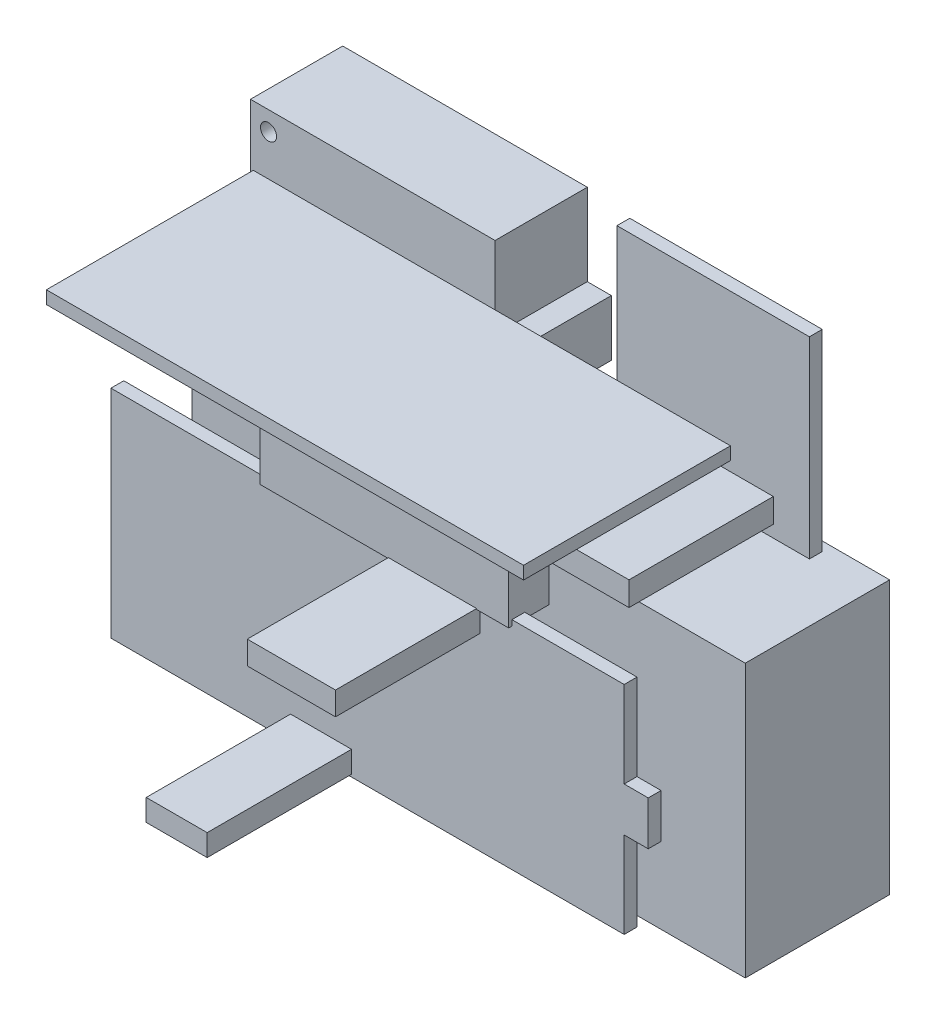
SolidWorks part; units mm, degrees
ref_plane "前视基准面" through (0, 0, 0) normal (0, 0, 1) x (1, 0, 0)
ref_plane "上视基准面" through (0, 0, 0) normal (0, 1, 0) x (1, 0, 0)
ref_plane "右视基准面" through (0, 0, 0) normal (1, 0, 0) x (0, 0, -1)
other "Configuration Table"
sketch "Battery holder 69 x 34 x 18 profile" plane through (0, 0, 0) normal (0, 0, 1) x (1, 0, 0)
  line L0 (-34.5, -29.75) -> (34.5, -29.75)
  line L1 (34.5, -29.75) -> (34.5, 4.25)
  line L2 (34.5, 4.25) -> (-34.5, 4.25)
  line L3 (-34.5, 4.25) -> (-34.5, -29.75)
extrude "Battery holder 69 x 34 x 18" add sketch "Battery holder 69 x 34 x 18 profile" along normal blind 18 from offset 4 separate body
sketch "YBX board 24 x 24 profile" plane through (0, 0, 0) normal (0, 0, 1) x (1, 0, 0)
  line L0 (4.5, 5.5) -> (28.5, 5.5)
  line L1 (28.5, 5.5) -> (28.5, 29.5)
  line L2 (28.5, 29.5) -> (4.5, 29.5)
  line L3 (4.5, 29.5) -> (4.5, 5.5)
extrude "YBX board 24 x 24" add sketch "YBX board 24 x 24 profile" along normal blind 1.6 from offset 6.4 separate body
sketch "YBX jumper allowance profile" plane through (0, 0, 0) normal (0, 0, 1) x (1, 0, 0)
  line L0 (9, 7) -> (24, 7)
  line L1 (24, 7) -> (24, 10)
  line L2 (24, 10) -> (9, 10)
  line L3 (9, 10) -> (9, 7)
extrude "YBX jumper allowance" add sketch "YBX jumper allowance profile" along normal blind 18 from offset 8 separate body
sketch "GNSS 11.5 mm high - 3 mm projection - D2 mount holes profile" plane through (0, 0, 0) normal (0, 0, 1) x (1, 0, 0)
  line L0 (-31.3, 4.7) -> (-0.8, 4.7)
  line L1 (-0.8, 4.7) -> (-0.8, 13)
  line L2 (-0.8, 13) -> (2.2, 13)
  line L3 (2.2, 13) -> (2.2, 20)
  line L4 (2.2, 20) -> (-0.8, 20)
  line L5 (-0.8, 20) -> (-0.8, 30.2)
  line L6 (-0.8, 30.2) -> (-31.3, 30.2)
  line L7 (-31.3, 30.2) -> (-31.3, 4.7)
  circle A0 centre (-29.05, 7) radius 1
  circle A1 centre (-29.05, 27.8) radius 1
extrude "GNSS 11.5 mm high - 3 mm projection - D2 mount holes" add sketch "GNSS 11.5 mm high - 3 mm projection - D2 mount holes profile" along normal blind 11.5 from offset 6.4 separate body
sketch "Power board 59.5 x 25.8 profile" plane through (0, 0, 0) normal (0, 0, 1) x (1, 0, 0)
  line L0 (-29.75, 22.3) -> (29.75, 22.3)
  line L1 (29.75, 22.3) -> (29.75, 23.9)
  line L2 (29.75, 23.9) -> (-29.75, 23.9)
  line L3 (-29.75, 23.9) -> (-29.75, 22.3)
extrude "Power board 59.5 x 25.8" add sketch "Power board 59.5 x 25.8 profile" along normal blind 25.8 from offset 19.1 separate body
sketch "Power horizontal connector allowance profile" plane through (0, 0, 0) normal (0, 0, 1) x (1, 0, 0)
  line L0 (-13, 6.3) -> (18, 6.3)
  line L1 (18, 6.3) -> (18, 22.3)
  line L2 (18, 22.3) -> (-13, 22.3)
  line L3 (-13, 22.3) -> (-13, 6.3)
extrude "Power horizontal connector allowance" add sketch "Power horizontal connector allowance profile" along normal blind 5 from offset 30 separate body
sketch "EoRa 64 x 27 - top projection 3 x 5.5 profile" plane through (0, 0, 0) normal (0, 0, 1) x (1, 0, 0)
  line L0 (-32, -20) -> (32, -20)
  line L1 (32, -20) -> (32, -9.25)
  line L2 (32, -9.25) -> (35, -9.25)
  line L3 (35, -9.25) -> (35, -3.75)
  line L4 (35, -3.75) -> (32, -3.75)
  line L5 (32, -3.75) -> (32, 7)
  line L6 (32, 7) -> (-32, 7)
  line L7 (-32, 7) -> (-32, -20)
extrude "EoRa 64 x 27 - top projection 3 x 5.5" add sketch "EoRa 64 x 27 - top projection 3 x 5.5 profile" along normal blind 1.6 from offset 33 separate body
sketch "EoRa jumper allowance A profile" plane through (0, 0, 0) normal (0, 0, 1) x (1, 0, 0)
  line L0 (-9.6, -19.7) -> (-2, -19.7)
  line L1 (-2, -19.7) -> (-2, -17)
  line L2 (-2, -17) -> (-9.6, -17)
  line L3 (-9.6, -17) -> (-9.6, -19.7)
extrude "EoRa jumper allowance A" add sketch "EoRa jumper allowance A profile" along normal blind 18 from offset 34.6 separate body
sketch "EoRa jumper allowance B profile" plane through (0, 0, 0) normal (0, 0, 1) x (1, 0, 0)
  line L0 (3, 3.5) -> (14, 3.5)
  line L1 (14, 3.5) -> (14, 6.4)
  line L2 (14, 6.4) -> (3, 6.4)
  line L3 (3, 6.4) -> (3, 3.5)
extrude "EoRa jumper allowance B" add sketch "EoRa jumper allowance B profile" along normal blind 18 from offset 34.6 separate body
